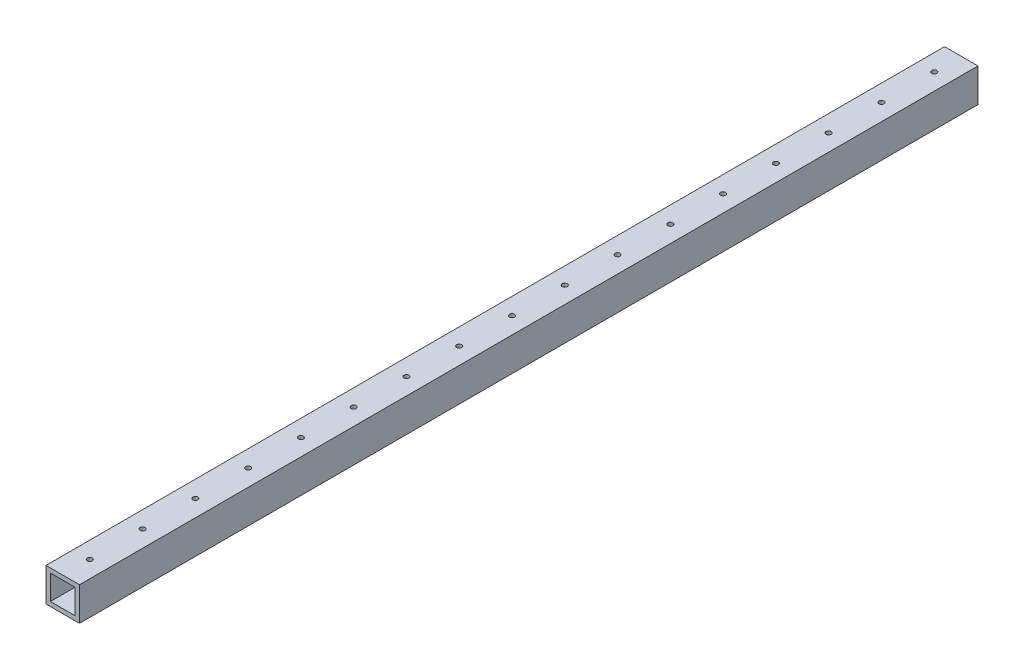
SolidWorks part; units mm, degrees
ref_plane "Alzado" through (0, 0, 0) normal (0, 0, 1) x (1, 0, 0)
ref_plane "Planta" through (0, 0, 0) normal (0, 1, 0) x (1, 0, 0)
ref_plane "Vista lateral" through (0, 0, 0) normal (1, 0, 0) x (0, 0, -1)
sketch "Croquis1" plane through (0, 0, 0) normal (0, 0, 1) x (1, 0, 0)
  line L0 (19, 19) -> (-19, -19) construction
  line L1 (-19, 19) -> (19, 19)
  line L2 (-19, 19) -> (-19, -19)
  line L3 (-19, -19) -> (19, -19)
  line L4 (19, 19) -> (19, -19)
  line L6 (-14, 14) -> (14, 14)
  line L7 (-14, 14) -> (-14, -14)
  line L8 (-14, -14) -> (14, -14)
  line L9 (14, 14) -> (14, -14)
  dimension "D1" = 38
  dimension "D2" = 38
  dimension "D3" = 5
  dimension "D4" = 5
  dimension "D5" = 5
  dimension "D6" = 5
extrude "Saliente-Extruir1" add sketch "Croquis1" along normal blind 1020
sketch "Croquis2" plane through (0, 19, 0) normal (0, 1, 0) x (1, 0, 0)
  line L0 (0, 0) -> (0, -1020) construction
  line L1 (19, -1020) -> (-19, -1020) construction
  circle A0 centre (0, -30.72) radius 2.87
  circle A1 centre (0, -90.63) radius 2.87
  circle A2 centre (0, -150.54) radius 2.87
  circle A3 centre (0, -210.45) radius 2.87
  circle A4 centre (0, -270.36) radius 2.87
  circle A5 centre (0, -330.27) radius 2.87
  circle A6 centre (0, -390.18) radius 2.87
  circle A7 centre (0, -450.09) radius 2.87
  circle A8 centre (0, -510) radius 2.87
  circle A9 centre (0, -569.91) radius 2.87
  circle A10 centre (0, -629.82) radius 2.87
  circle A11 centre (0, -689.73) radius 2.87
  circle A12 centre (0, -749.64) radius 2.87
  circle A13 centre (0, -809.55) radius 2.87
  circle A14 centre (0, -869.46) radius 2.87
  circle A15 centre (0, -929.37) radius 2.87
  circle A16 centre (0, -989.28) radius 2.87
  dimension "D1" = 5.74
  dimension "D2" = 30.72
  dimension "D3" = 17
extrude "Cortar-Extruir1" cut sketch "Croquis2" against normal up to surface (561.0847 mm away)
